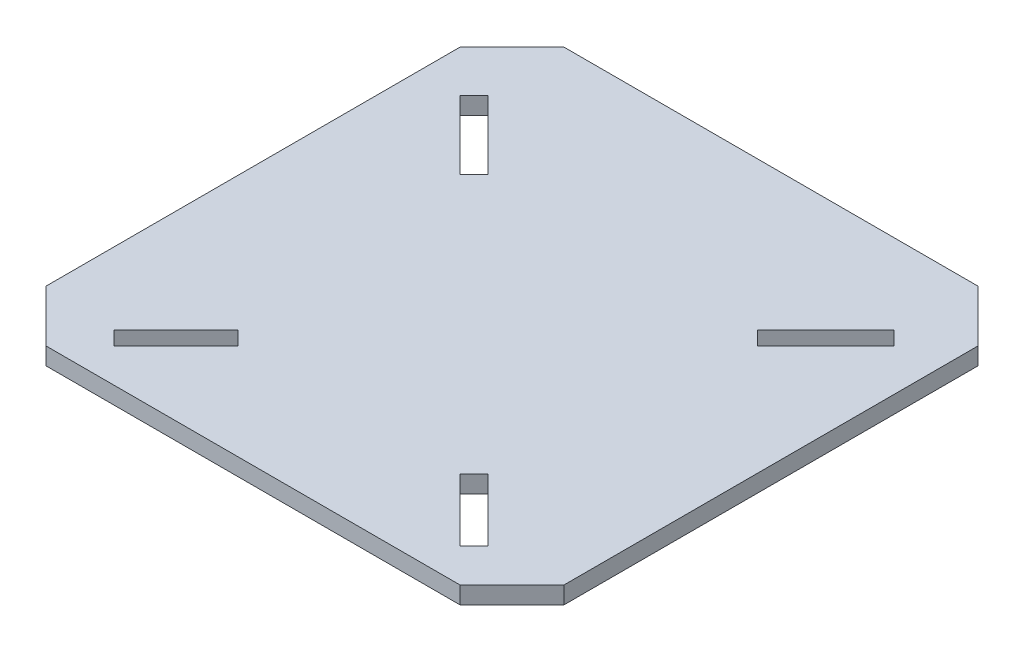
SolidWorks part; units mm, degrees
ref_plane "前视基准面" through (0, 0, 0) normal (0, 0, 1) x (1, 0, 0)
ref_plane "上视基准面" through (0, 0, 0) normal (0, 1, 0) x (1, 0, 0)
ref_plane "右视基准面" through (0, 0, 0) normal (1, 0, 0) x (0, 0, -1)
other "Configuration Table"
sketch "草图1" plane through (0, 0, 0) normal (0, 1, 0) x (1, 0, 0)
  line L0 (-27, 30) -> (-30, 27)
  line L1 (-3, 0) -> (-27, 0)
  line L2 (0, 3) -> (0, 27)
  line L3 (-3, 30) -> (-27, 30)
  line L4 (-30, 3) -> (-30, 27)
  line L5 (0, 27) -> (-3, 30)
  line L6 (-3, 0) -> (0, 3)
  line L7 (-27, 0) -> (-30, 3)
  point P0 (0, 0)
  point P1 (-30, 30)
  point P2 (0, 30)
  point P3 (-30, 0)
extrude "凸台-拉伸1" add sketch "草图1" along normal blind 1
sketch "草图2" plane through (0, 0, 0) normal (0, 1, 0) x (1, 0, 0)
  line L12 (-26.7685, 25.3752) -> (-27.5719, 24.5719)
  line L13 (-27.5719, 24.5719) -> (-23.6084, 20.6084)
  line L14 (-23.6084, 20.6084) -> (-22.8051, 21.4118)
  line L15 (-22.8051, 21.4118) -> (-26.7685, 25.3752)
  line L16 (-3.2315, 25.3752) -> (-2.4281, 24.5719)
  line L17 (-2.4281, 24.5719) -> (-6.3916, 20.6084)
  line L18 (-6.3916, 20.6084) -> (-7.1949, 21.4118)
  line L19 (-7.1949, 21.4118) -> (-3.2315, 25.3752)
  line L20 (-25.8351, 2.7716) -> (-25.0318, 1.9682)
  line L21 (-25.0318, 1.9682) -> (-21.4336, 5.5664)
  line L22 (-21.4336, 5.5664) -> (-22.2369, 6.3698)
  line L23 (-22.2369, 6.3698) -> (-25.8351, 2.7716)
  line L26 (-4.9682, 1.9682) -> (-4.1649, 2.7716)
  line L27 (-4.1649, 2.7716) -> (-7.7632, 6.3699)
  line L28 (-7.7632, 6.3699) -> (-8.5666, 5.5666)
  line L31 (-4.9682, 1.9682) -> (-8.5666, 5.5666)
  point P33 (-8.5741, 5.5464)
extrude "切除-拉伸1" cut sketch "草图2" along normal blind 1
